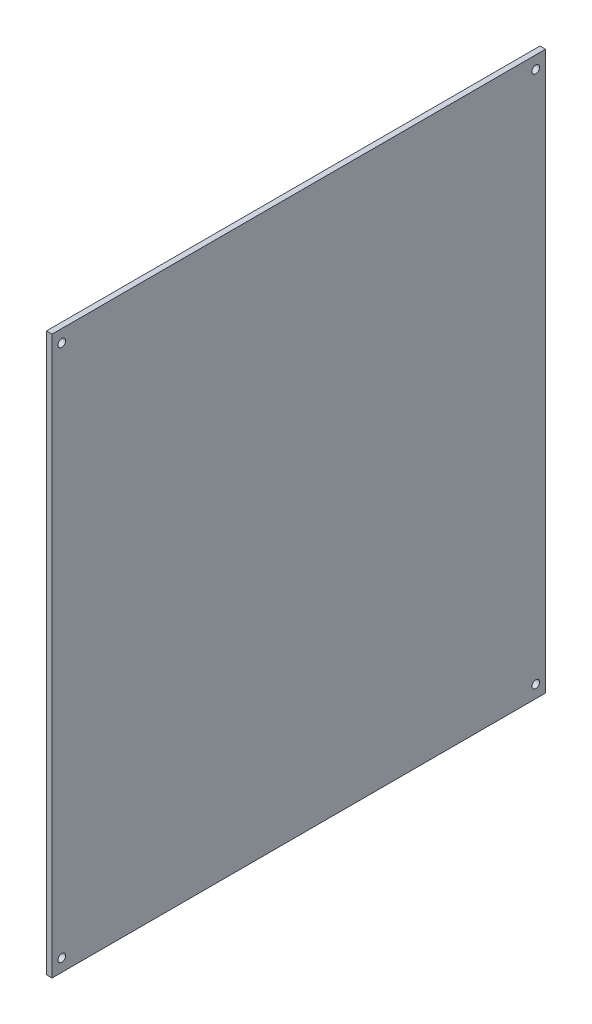
SolidWorks part; units mm, degrees
ref_plane "前视基准面" through (0, 0, 0) normal (0, 0, 1) x (1, 0, 0)
ref_plane "上视基准面" through (0, 0, 0) normal (0, 1, 0) x (1, 0, 0)
ref_plane "右视基准面" through (0, 0, 0) normal (1, 0, 0) x (0, 0, -1)
other "Configuration Table"
sketch "草图1" plane through (0, 0, 0) normal (1, 0, 0) x (0, 0, -1)
  line L1 (0, 0) -> (354, 0)
  line L2 (0, 0) -> (0, 400)
  line L3 (0, 400) -> (354, 400)
  line L4 (354, 0) -> (354, 400)
  dimension "D1" = 354
  dimension "D2" = 400
extrude "凸台-拉伸1" add sketch "草图1" along normal blind 4
ref_plane "基准面1" through (0, 0, -177) normal (0, 0, -1) x (-1, 0, 0)
sketch "草图2" plane through (4, 0, 0) normal (1, 0, 0) x (0, 0, -1)
  line L0 (354, 400) -> (0, 400) construction
  line L1 (0, 400) -> (0, 0) construction
  line L2 (0, 0) -> (354, 0) construction
  line L3 (177, -2.2) -> (177, 2.2) construction
  circle A0 centre (7, 391) radius 2.75
  circle A1 centre (7, 9) radius 2.75
  circle A2 centre (347, 9) radius 2.75
  circle A3 centre (347, 391) radius 2.75
  dimension "D1" = 9
  dimension "D2" = 7
  dimension "D3" = 5.5
  dimension "D4" = 5.5
  dimension "D5" = 9
  dimension "D6" = 7
extrude "切除-拉伸1" cut sketch "草图2" against normal blind 4
